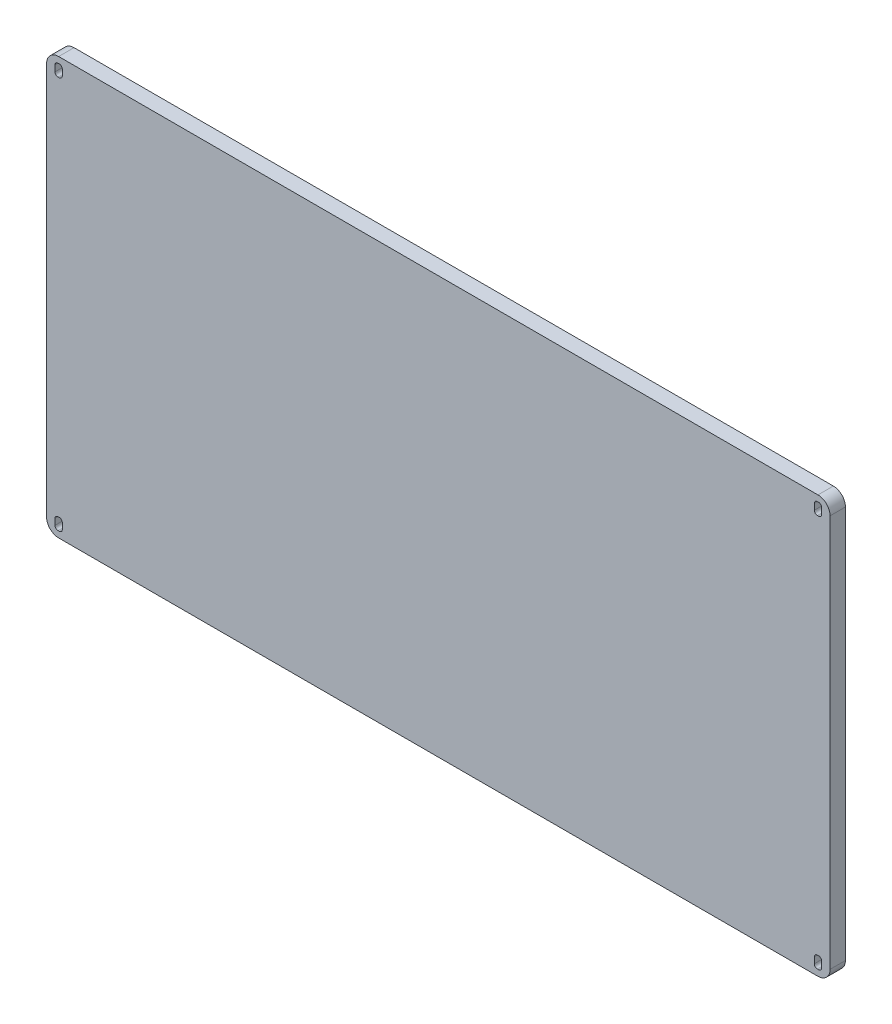
SolidWorks part; units mm, degrees
ref_plane "Front Plane" through (0, 0, 0) normal (0, 0, 1) x (1, 0, 0)
ref_plane "Top Plane" through (0, 0, 0) normal (0, 1, 0) x (1, 0, 0)
ref_plane "Right Plane" through (0, 0, 0) normal (1, 0, 0) x (0, 0, -1)
sketch "Sketch1" plane through (0, 0, 0) normal (0, 0, 1) x (1, 0, 0)
  line L0 (339.8604, -207.3242) -> (338.8604, -207.3242)
  line L1 (-298.3396, 132.3538) -> (349.3604, 132.3538)
  line L2 (-298.3396, 132.3538) -> (-298.3396, -212.3242)
  line L3 (-298.3396, -212.3242) -> (349.3604, -212.3242)
  line L4 (349.3604, 132.3538) -> (349.3604, -212.3242)
  line L5 (342.3604, -204.8242) -> (342.3604, -199.8242)
  line L6 (339.8604, -197.3242) -> (338.8604, -197.3242)
  line L7 (336.3604, -204.8242) -> (336.3604, -199.8242)
  line L8 (339.3604, -197.3242) -> (339.3604, -207.3242) construction
  line L9 (336.3604, -202.3242) -> (342.3604, -202.3242) construction
  line L10 (-287.8396, -207.3242) -> (-288.8396, -207.3242)
  line L11 (-291.3396, -204.8242) -> (-291.3396, -199.8242)
  line L12 (-287.8396, -197.3242) -> (-288.8396, -197.3242)
  line L13 (-285.3396, -204.8242) -> (-285.3396, -199.8242)
  line L14 (-287.8396, 117.3558) -> (-288.8396, 117.3558)
  line L15 (-291.3396, 119.8558) -> (-291.3396, 124.8558)
  line L16 (-287.8396, 127.3558) -> (-288.8396, 127.3558)
  line L17 (-285.3396, 119.8558) -> (-285.3396, 124.8558)
  line L18 (339.8604, 117.3558) -> (338.8604, 117.3558)
  line L19 (336.3604, 119.8558) -> (336.3604, 124.8558)
  line L20 (339.8604, 127.3558) -> (338.8604, 127.3558)
  line L21 (342.3604, 119.8558) -> (342.3604, 124.8558)
  arc A0 (339.8604, -207.3242) -> (342.3604, -204.8242) centre (339.8604, -204.8242) ccw
  arc A1 (342.3604, -199.8242) -> (339.8604, -197.3242) centre (339.8604, -199.8242) ccw
  arc A2 (338.8604, -207.3242) -> (336.3604, -204.8242) centre (338.8604, -204.8242) cw
  arc A3 (338.8604, -197.3242) -> (336.3604, -199.8242) centre (338.8604, -199.8242) ccw
  arc A4 (-288.8396, -207.3242) -> (-291.3396, -204.8242) centre (-288.8396, -204.8242) cw
  arc A5 (-288.8396, -197.3242) -> (-291.3396, -199.8242) centre (-288.8396, -199.8242) ccw
  arc A6 (-285.3396, -199.8242) -> (-287.8396, -197.3242) centre (-287.8396, -199.8242) ccw
  arc A7 (-287.8396, -207.3242) -> (-285.3396, -204.8242) centre (-287.8396, -204.8242) ccw
  arc A8 (-288.8396, 117.3558) -> (-291.3396, 119.8558) centre (-288.8396, 119.8558) cw
  arc A9 (-288.8396, 127.3558) -> (-291.3396, 124.8558) centre (-288.8396, 124.8558) ccw
  arc A10 (-285.3396, 124.8558) -> (-287.8396, 127.3558) centre (-287.8396, 124.8558) ccw
  arc A11 (-287.8396, 117.3558) -> (-285.3396, 119.8558) centre (-287.8396, 119.8558) ccw
  arc A12 (338.8604, 117.3558) -> (336.3604, 119.8558) centre (338.8604, 119.8558) cw
  arc A13 (338.8604, 127.3558) -> (336.3604, 124.8558) centre (338.8604, 124.8558) ccw
  arc A14 (342.3604, 124.8558) -> (339.8604, 127.3558) centre (339.8604, 124.8558) ccw
  arc A15 (339.8604, 117.3558) -> (342.3604, 119.8558) centre (339.8604, 119.8558) ccw
  point P16 (339.3604, -207.3242)
  dimension "D6" = 2.5
  dimension "D1" = 647.7
  dimension "D2" = 132.3538
  dimension "12in" = 344.678
  dimension "D3" = 298.3396
  dimension "D4" = 6
  dimension "D5" = 10
  dimension "D7" = 10
  dimension "D8" = 10
  dimension "D11" = 7
  dimension "D12" = 4.998
  dimension "D13" = 7
  dimension "D9" = 2
  dimension "D10" = 2
extrude "Boss-Extrude1" add sketch "Sketch1" along normal blind 12.7
fillet "Fillet1" radius 10 3 edges at (349.3604, -212.3242, 6.35) (349.3604, 132.3538, 6.35) (-298.3396, 132.3538, 6.35)
fillet "Fillet2" radius 10 1 edges at (-298.3396, -212.3242, 6.35)
